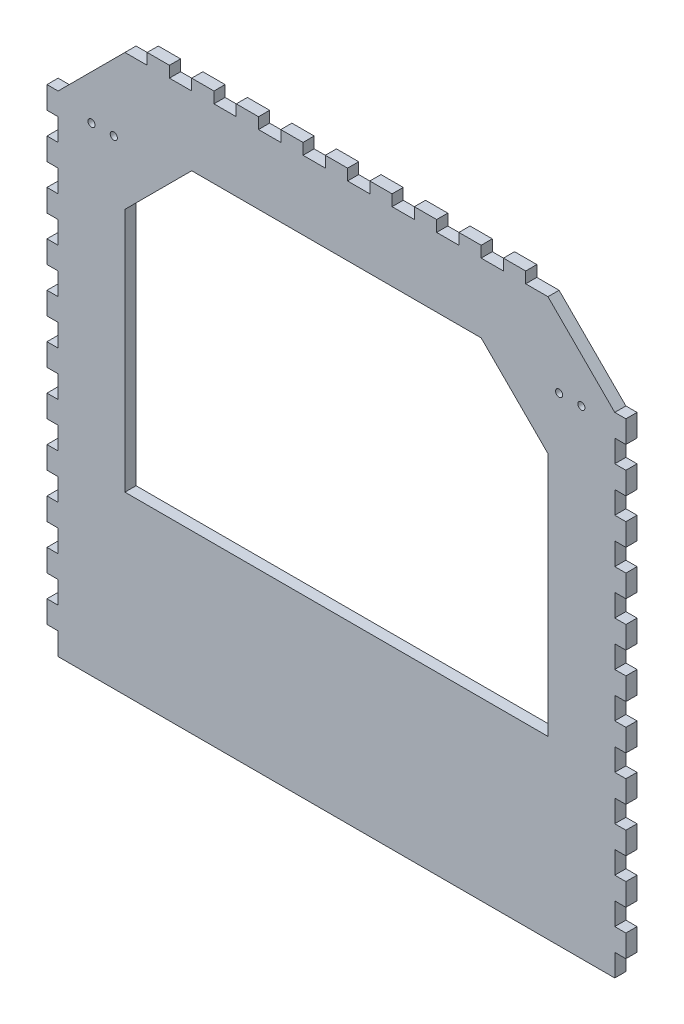
SolidWorks part; units mm, degrees
material "Buche"
ref_plane "Ebene vorne" through (0, 0, 0) normal (0, 0, 1) x (1, 0, 0)
ref_plane "Ebene oben" through (0, 0, 0) normal (0, 1, 0) x (1, 0, 0)
ref_plane "Ebene rechts" through (0, 0, 0) normal (1, 0, 0) x (0, 0, -1)
sketch "Skizze1" plane through (0, 0, 0) normal (0, 0, 1) x (1, 0, 0)
  line L0 (35, 250) -> (45, 250)
  line L1 (45, 250) -> (45, 255)
  line L2 (45, 255) -> (55, 255)
  line L3 (55, 255) -> (55, 250)
  line L4 (55, 250) -> (65, 250)
  line L5 (65, 250) -> (65, 255)
  line L6 (65, 255) -> (75, 255)
  line L7 (75, 255) -> (75, 250)
  line L8 (75, 250) -> (85, 250)
  line L9 (85, 250) -> (85, 255)
  line L10 (85, 255) -> (95, 255)
  line L11 (95, 255) -> (95, 250)
  line L12 (95, 250) -> (105, 250)
  line L13 (105, 250) -> (105, 255)
  line L14 (105, 255) -> (115, 255)
  line L15 (115, 255) -> (115, 250)
  line L16 (115, 250) -> (125, 250)
  line L17 (125, 250) -> (125, 255)
  line L18 (125, 255) -> (135, 255)
  line L19 (135, 255) -> (135, 250)
  line L20 (135, 250) -> (145, 250)
  line L21 (145, 250) -> (145, 255)
  line L22 (145, 255) -> (155, 255)
  line L23 (155, 255) -> (155, 250)
  line L24 (155, 250) -> (165, 250)
  line L25 (165, 250) -> (165, 255)
  line L26 (165, 255) -> (175, 255)
  line L27 (175, 255) -> (175, 250)
  line L28 (175, 250) -> (185, 250)
  line L29 (185, 250) -> (185, 255)
  line L30 (185, 255) -> (195, 255)
  line L31 (195, 255) -> (195, 250)
  line L32 (195, 250) -> (205, 250)
  line L33 (205, 250) -> (205, 255)
  line L34 (205, 255) -> (215, 255)
  line L35 (215, 255) -> (215, 250)
  line L36 (215, 250) -> (225, 250)
  line L197 (255, 220) -> (260, 220)
  line L198 (260, 220) -> (260, 210)
  line L199 (5, 190) -> (5, 180)
  line L200 (65, 218.9712) -> (195, 218.9712)
  line L201 (255, 210) -> (255, 200)
  line L202 (255, 200) -> (260, 200)
  line L203 (260, 200) -> (260, 190)
  line L204 (5, 200) -> (0, 200)
  line L205 (5, 210) -> (5, 200)
  line L206 (0, 190) -> (5, 190)
  line L207 (35, 78.9712) -> (35, 188.9712)
  line L208 (255, 190) -> (255, 180)
  line L209 (260, 190) -> (255, 190)
  line L210 (0, 200) -> (0, 190)
  line L211 (5, 170) -> (5, 160)
  line L212 (5, 180) -> (0, 180)
  line L213 (0, 170) -> (5, 170)
  line L214 (5, 220) -> (35, 250)
  line L215 (255, 180) -> (260, 180)
  line L216 (260, 180) -> (260, 170)
  line L217 (255, 170) -> (255, 160)
  line L218 (0, 180) -> (0, 170)
  line L219 (5, 220) -> (0, 220)
  line L220 (260, 170) -> (255, 170)
  line L221 (255, 160) -> (260, 160)
  line L222 (5, 150) -> (5, 140)
  line L223 (5, 160) -> (0, 160)
  line L224 (225, 188.9712) -> (195, 218.9712)
  line L225 (260, 160) -> (260, 150)
  line L226 (255, 150) -> (255, 140)
  line L227 (260, 150) -> (255, 150)
  line L228 (0, 150) -> (5, 150)
  line L229 (0, 160) -> (0, 150)
  line L230 (255, 140) -> (260, 140)
  line L231 (260, 140) -> (260, 130)
  line L232 (260, 210) -> (255, 210)
  line L233 (5, 130) -> (5, 120)
  line L234 (5, 140) -> (0, 140)
  line L235 (0, 210) -> (5, 210)
  line L236 (0, 130) -> (5, 130)
  line L237 (255, 130) -> (255, 120)
  line L238 (0, 140) -> (0, 130)
  line L239 (5, 110) -> (5, 100)
  line L240 (5, 120) -> (0, 120)
  line L241 (35, 78.9712) -> (225, 78.9712)
  line L242 (260, 130) -> (255, 130)
  line L243 (255, 120) -> (260, 120)
  line L244 (260, 120) -> (260, 110)
  line L245 (255, 110) -> (255, 100)
  line L246 (260, 110) -> (255, 110)
  line L247 (0, 110) -> (5, 110)
  line L248 (0, 120) -> (0, 110)
  line L249 (5, 90) -> (5, 80)
  line L250 (5, 100) -> (0, 100)
  line L251 (0, 90) -> (5, 90)
  line L252 (5, 0) -> (255, 0)
  line L253 (35, 188.9712) -> (65, 218.9712)
  line L254 (255, 100) -> (260, 100)
  line L255 (260, 100) -> (260, 90)
  line L256 (255, 90) -> (255, 80)
  line L257 (260, 90) -> (255, 90)
  line L258 (255, 80) -> (260, 80)
  line L259 (260, 80) -> (260, 70)
  line L260 (0, 100) -> (0, 90)
  line L261 (5, 70) -> (5, 60)
  line L262 (255, 70) -> (255, 60)
  line L263 (225, 78.9712) -> (225, 188.9712)
  line L264 (260, 70) -> (255, 70)
  line L265 (5, 80) -> (0, 80)
  line L266 (0, 70) -> (5, 70)
  line L267 (0, 80) -> (0, 70)
  line L268 (5, 50) -> (5, 40)
  line L269 (255, 60) -> (260, 60)
  line L270 (260, 60) -> (260, 50)
  line L271 (255, 50) -> (255, 40)
  line L272 (5, 60) -> (0, 60)
  line L273 (0, 50) -> (5, 50)
  line L274 (255, 220) -> (225, 250)
  line L275 (260, 50) -> (255, 50)
  line L276 (255, 40) -> (260, 40)
  line L277 (0, 60) -> (0, 50)
  line L278 (5, 30) -> (5, 20)
  line L279 (0, 220) -> (0, 210)
  line L280 (5, 40) -> (0, 40)
  line L281 (260, 40) -> (260, 30)
  line L282 (255, 30) -> (255, 20)
  line L283 (260, 30) -> (255, 30)
  line L284 (255, 20) -> (260, 20)
  line L285 (260, 20) -> (260, 10)
  line L286 (0, 30) -> (5, 30)
  line L287 (255, 10) -> (255, 0)
  line L288 (260, 10) -> (255, 10)
  line L289 (0, 40) -> (0, 30)
  line L290 (5, 10) -> (5, 0)
  line L291 (5, 20) -> (0, 20)
  line L292 (0, 10) -> (5, 10)
  line L293 (0, 20) -> (0, 10)
  circle A0 centre (20, 215) radius 1.6
  circle A1 centre (30, 215) radius 1.6
  circle A2 centre (240, 215) radius 1.6
  circle A3 centre (230, 215) radius 1.6
  point P3 (0, 0)
  dimension "D1" = 9
extrude "Aufsatz-Linear austragen1" add sketch "Skizze1" along normal blind 5
